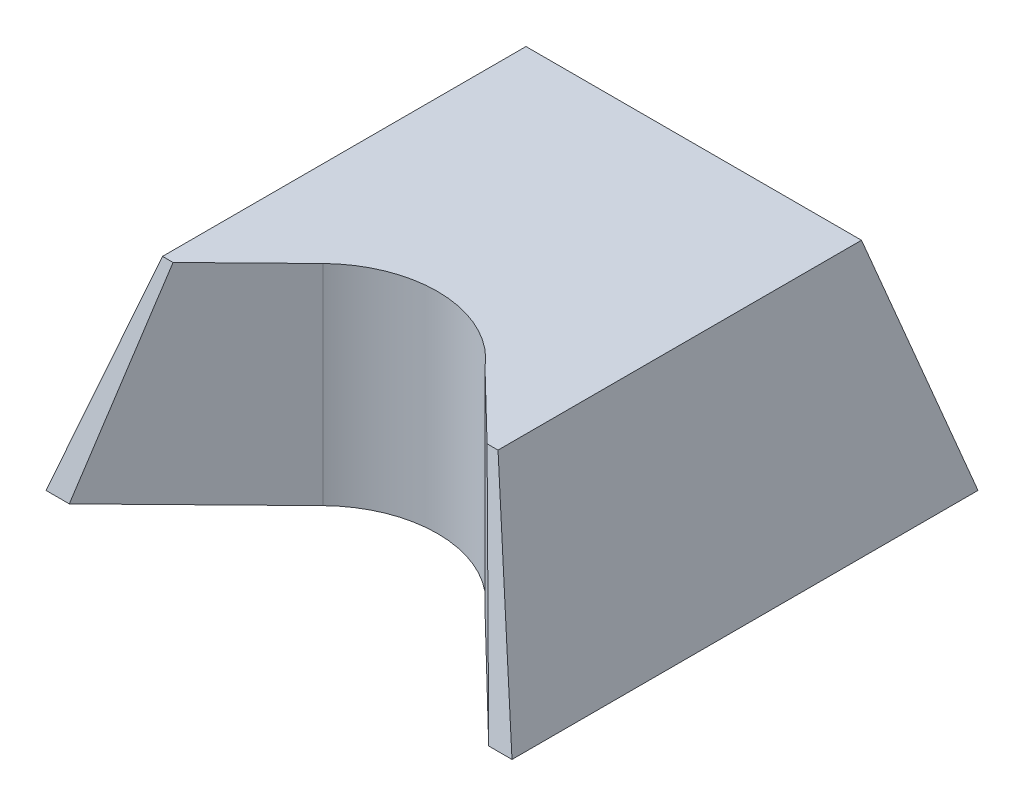
SolidWorks part; units mm, degrees
ref_plane "Ebene vorne" through (0, 0, 0) normal (0, 0, 1) x (1, 0, 0)
ref_plane "Ebene oben" through (0, 0, 0) normal (0, 1, 0) x (1, 0, 0)
ref_plane "Ebene rechts" through (0, 0, 0) normal (1, 0, 0) x (0, 0, -1)
sketch "Skizze1" plane through (0, 0, 0) normal (0, 0, 1) x (1, 0, 0)
  line L0 (0, 0) -> (100, 0)
  line L1 (100, 0) -> (86, 45)
  line L2 (86, 45) -> (14, 45)
  line L3 (14, 45) -> (0, 0)
  dimension "D1" = 100
  dimension "D2" = 14
  dimension "D3" = 14
  dimension "D4" = 45
extrude "Grundkörper" add sketch "Skizze1" against normal blind 100
sketch "Skizze2" plane through (0, 0, 0) normal (1, 0, 0) x (0, 0, -1)
  line L0 (100, 0) -> (89, 45)
  line L1 (100, 45) -> (0, 45) construction
  line L2 (89, 45) -> (100, 45)
  line L3 (100, 45) -> (100, 0)
  dimension "D1" = 11
extrude "Schraegen_vorne" cut sketch "Skizze2" along normal blind 100
ref_plane "Ebene1" through (0, 0, -50) normal (0, 0, 1) x (1, 0, 0)
mirror "Spiegel_Schraege_hinten" about plane through (0, 0, -50) normal (0, 0, 1) of "Schraegen_vorne"
sketch "Skizze4" plane through (0, 0, 0) normal (0, -1, 0) x (1, 0, 0)
  line L7 (5, 0) -> (95, 0)
  line L8 (0, 0) -> (100, 0) construction
  line L12 (5, 0) -> (32.5338, -26.8866)
  line L13 (69.2293, -24.976) -> (95, 0)
  line L14 (0, -100) -> (0, 0) construction
  arc A0 (32.5338, -26.8866) -> (69.2293, -24.976) centre (50, -9) ccw
  point P7 (50, 0)
  dimension "D2" = 9
  dimension "D6" = 25
  dimension "D1" = 90
  dimension "D4" = 5
  dimension "D5" = 50
extrude "Schnitt-Linear austragen4" cut sketch "Skizze4" against normal blind 45
shell "Wandung1" thickness 1.75
ref_plane "Ebene2" through (98.1673, 0, -98.1985) normal (-0.2893, 0.9299, 0.2273) x (0.9572, 0.281, 0.0687)
ref_plane "Ebene3" through (0, 9, 0) normal (0, -1, 0) x (-1, 0, 0)
ref_plane "Ebene4" through (0, 0, 0) normal (-1, 0, 0) x (0, 0, 1)
ref_plane "Ebene5" through (27, 0, 0) normal (-1, 0, 0) x (0, 0, 1)
sketch "Skizze5" plane through (27, 0, 0) normal (-1, 0, 0) x (0, 0, 1)
  line L0 (-90.9985, 9) -> (-95.9985, 9)
  line L1 (-54.9769, 9) -> (54.9769, 9) construction
  line L2 (-98.1985, 0) -> (-87.6263, 43.25) construction
  line L3 (-95.9985, 9) -> (-96.6096, 6.5)
  line L4 (-96.6096, 6.5) -> (-90.9985, 6.5)
  line L5 (-90.9985, 6.5) -> (-90.9985, 9)
  dimension "D1" = 2.5
  dimension "D2" = 5
extrude "Aufsatz-Linear austragen1" add sketch "Skizze5" against normal blind 40
ref_plane "Ebene6" through (50, 0, 0) normal (-1, 0, 0) x (0, 0, 1)
ref_plane "Ebene7" through (0, 12.75, 0) normal (0, -1, 0) x (-1, 0, 0)
sketch "Skizze10" plane through (0, 12.75, 0) normal (0, -1, 0) x (-1, 0, 0)
  line L0 (-45, 35.2786) -> (-45, 39)
  line L1 (-55, 39) -> (-55, 35.2786)
  line L4 (-25.913, 50) -> (25.913, 50) construction
  line L5 (-50, -24.75) -> (-50, 24.75) construction
  arc A1 (-45, 39) -> (-55, 39) centre (-50, 39) ccw
  arc A2 (-31.3112, 28.1387) -> (-70.5139, 26.1681) centre (-50, 9) ccw construction
  arc A3 (-45, 35.2786) -> (-55, 35.2786) centre (-50, 9) ccw
  point P8 (-56.0455, 35.0579)
  point P15 (-45, 35.2786)
  dimension "D2" = 11
  dimension "D1" = 5
  dimension "D4" = 5
  dimension "D3" = 10
extrude "Aufsatz-Linear austragen3" add sketch "Skizze10" against normal blind 3
sketch "Skizze12" plane through (0, 12.75, 0) normal (0, -1, 0) x (1, 0, 0)
  line L1 (46.6514, -39) -> (48.3257, -41.9)
  line L2 (48.3257, -41.9) -> (51.6743, -41.9)
  line L3 (51.6743, -41.9) -> (53.3486, -39)
  line L4 (53.3486, -39) -> (51.6743, -36.1)
  line L5 (51.6743, -36.1) -> (48.3257, -36.1)
  line L6 (48.3257, -36.1) -> (46.6514, -39)
  line L7 (25.913, -50) -> (-25.913, -50) construction
  circle A0 centre (50, -39) radius 2.9 construction
  point P1 (50, -44)
  dimension "D1" = 11
extrude "Schnitt-Linear austragen6" cut sketch "Skizze12" against normal blind 2.4
sketch "Skizze13" plane through (0, 15.75, 0) normal (0, 1, 0) x (1, 0, 0)
  line L1 (-25.913, 50) -> (25.913, 50) construction
  circle A0 centre (50, 39) radius 1.7
  point P3 (50, 44)
  point P4 (50, 41.2248)
  point P7 (50, 41.2478)
  dimension "D1" = 3.4
  dimension "D2" = 11
extrude "Schnitt-Linear austragen7" cut sketch "Skizze13" against normal blind 2.4
